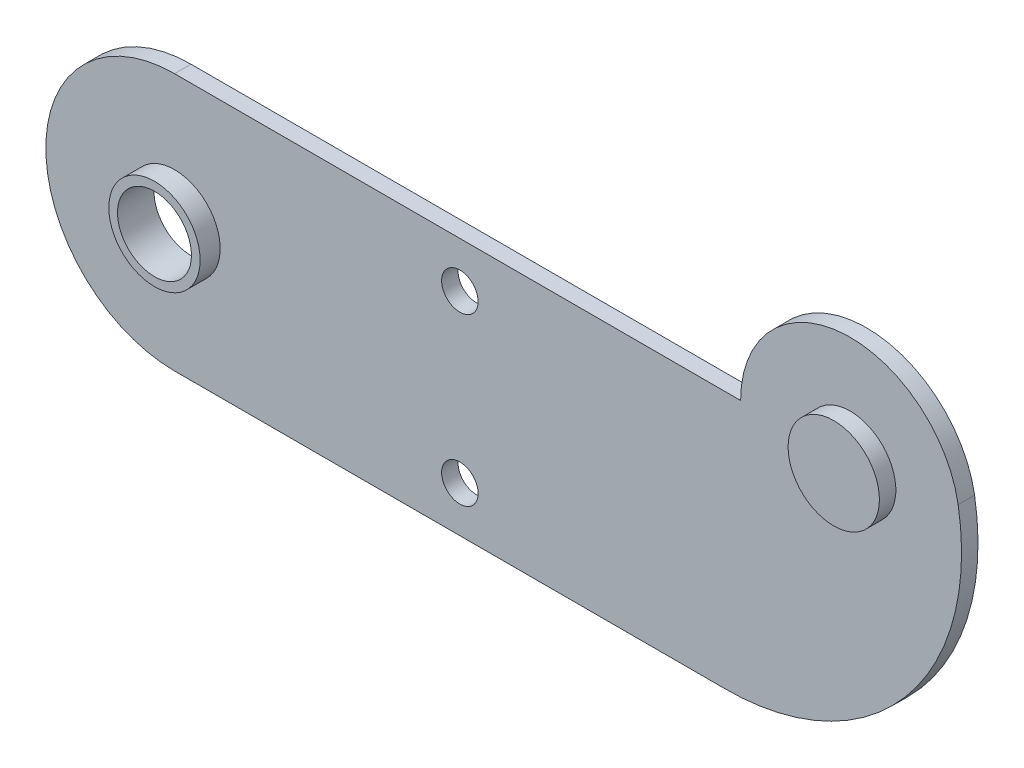
SolidWorks part; units mm, degrees
ref_plane "Plano frontal" through (0, 0, 0) normal (0, 0, 1) x (1, 0, 0)
ref_plane "Plano superior" through (0, 0, 0) normal (0, 1, 0) x (1, 0, 0)
ref_plane "Plano direito" through (0, 0, 0) normal (1, 0, 0) x (0, 0, -1)
sketch "Esboço1" plane through (0, 0, 0) normal (0, 0, 1) x (1, 0, 0)
  line L0 (-12, 0) -> (-74, 0)
  line L1 (-14, -28.2) -> (-74, -28.2)
  arc A0 (-12, 0) -> (11.8263, 2.0344) centre (0, 0) cw
  arc A1 (11.8263, 2.0344) -> (-14, -28.2) centre (-13.6532, -2.3486) cw
  arc A2 (-74, 0) -> (-74, -28.2) centre (-74, -14.1) ccw
  circle A3 centre (-74, -14.1) radius 4.05
  circle A4 centre (-42.75, -5) radius 2
  circle A5 centre (-42.75, -23.2) radius 2
  point P14 (0, 0)
  point P15 (0, 0)
  point P16 (0, 0)
  point P17 (0, 0)
  point P18 (0, 0)
  point P19 (0, 0)
  point P20 (0, 0)
  point P21 (-64.7859, -14.1)
  point P22 (-64.7859, -14.1)
  dimension "D1" = 28.2
  dimension "D2" = 12
  dimension "D3" = 31.25
  dimension "D4" = 5
  dimension "D5" = 5
extrude "Ressalto-extrusão1" add sketch "Esboço1" along normal blind 1.8
sketch "Esboço2" plane through (0, 0, 0) normal (0, 0, 1) x (1, 0, 0)
  circle A0 centre (0, 0) radius 5
extrude "Ressalto-extrusão2" add sketch "Esboço2" along normal blind 3.6
ref_plane "Plano1" through (0, 0, 1.8) normal (0, 0, 1) x (1, 0, 0)
sketch "Esboço4" plane through (0, 0, 1.8) normal (0, 0, 1) x (1, 0, 0)
  circle A0 centre (-74, -14.1) radius 5
  circle A1 centre (-74, -14.1) radius 4.05
extrude "Ressalto-extrusão3" add sketch "Esboço4" along normal blind 2.2
